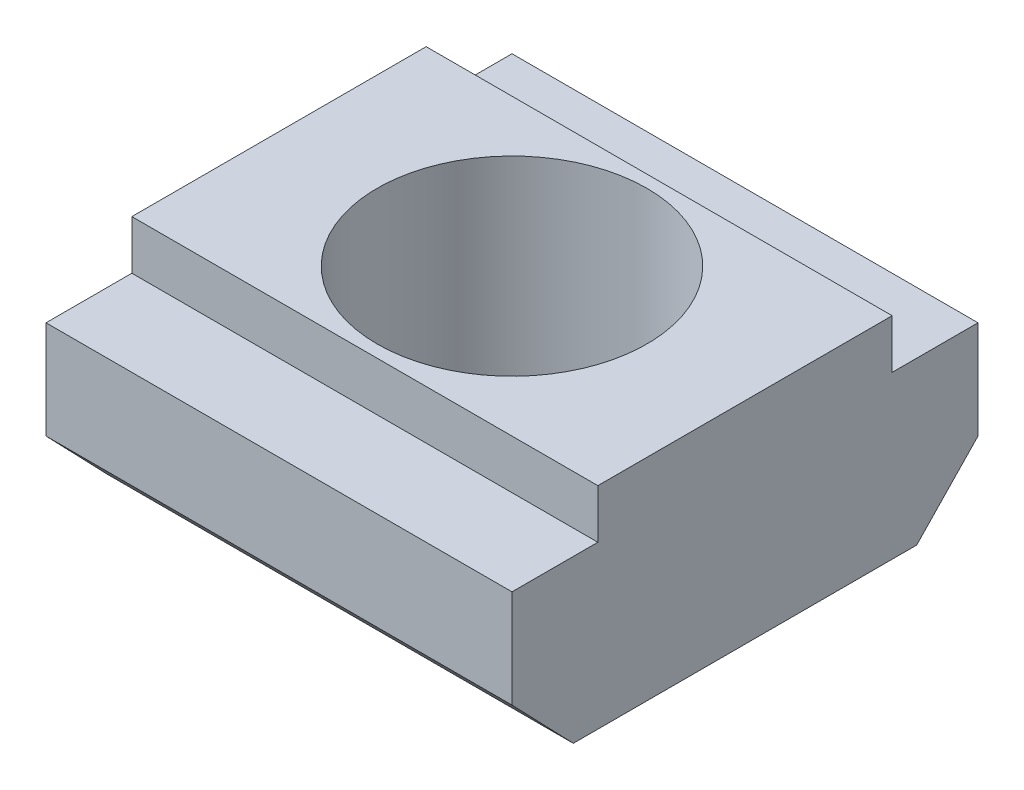
SolidWorks part; units mm, degrees
ref_plane "Front Plane" through (0, 0, 0) normal (0, 0, 1) x (1, 0, 0)
ref_plane "Top Plane" through (0, 0, 0) normal (0, 1, 0) x (1, 0, 0)
ref_plane "Right Plane" through (0, 0, 0) normal (1, 0, 0) x (0, 0, -1)
sketch "Sketch1" plane through (0, 0, 0) normal (1, 0, 0) x (0, 0, -1)
  line L0 (-3.5, 0) -> (3.5, 0)
  line L1 (3.5, 0) -> (4.75, 1.3)
  line L2 (4.75, 1.3) -> (4.75, 3.3)
  line L3 (4.75, 3.3) -> (3, 3.3)
  line L4 (3, 3.3) -> (3, 4.3)
  line L5 (3, 4.3) -> (-3, 4.3)
  line L6 (0, 4.1046) -> (0, 0) construction
  line L7 (-3, 3.3) -> (-3, 4.3)
  line L8 (-4.75, 3.3) -> (-3, 3.3)
  line L9 (-4.75, 1.3) -> (-4.75, 3.3)
  line L10 (-3.5, 0) -> (-4.75, 1.3)
  point P10 (4.75, 1.7058)
  point P12 (0, 4.3)
  point P16 (0, 0)
  dimension "D1" = 7
  dimension "D2" = 9.5
  dimension "D3" = 6
  dimension "D4" = 4.3
  dimension "D5" = 3.3
  dimension "D6" = 2
extrude "Body" add sketch "Sketch1" along normal mid plane 9.5
hole_wizard "M5 Clearance Hole1" positions "Sketch2" profile "Sketch3" hole size "M5" standard "ANSI Metric" end condition through all
sketch "Sketch2" plane through (0, 4.3, 0) normal (0, 1, 0) x (1, 0, 0)
  point P0 (0, 0)
  point P3 (0, 0)
sketch "Sketch3" plane through (0, 4.3, 0) normal (1, 0, 0) x (0, 0, 1)
  line L0 (0, 0) -> (0, 4.3)
  line L1 (0, 4.3) -> (2.75, 4.3)
  line L2 (2.75, 4.3) -> (2.75, 0)
  line L5 (2.75, 0) -> (0, 0)
  line L11 (0, -6.35) -> (0, 107.95) construction
  dimension "Thru Hole Dia." = 5.5
  dimension "Thru Hole Depth" = 4.3
